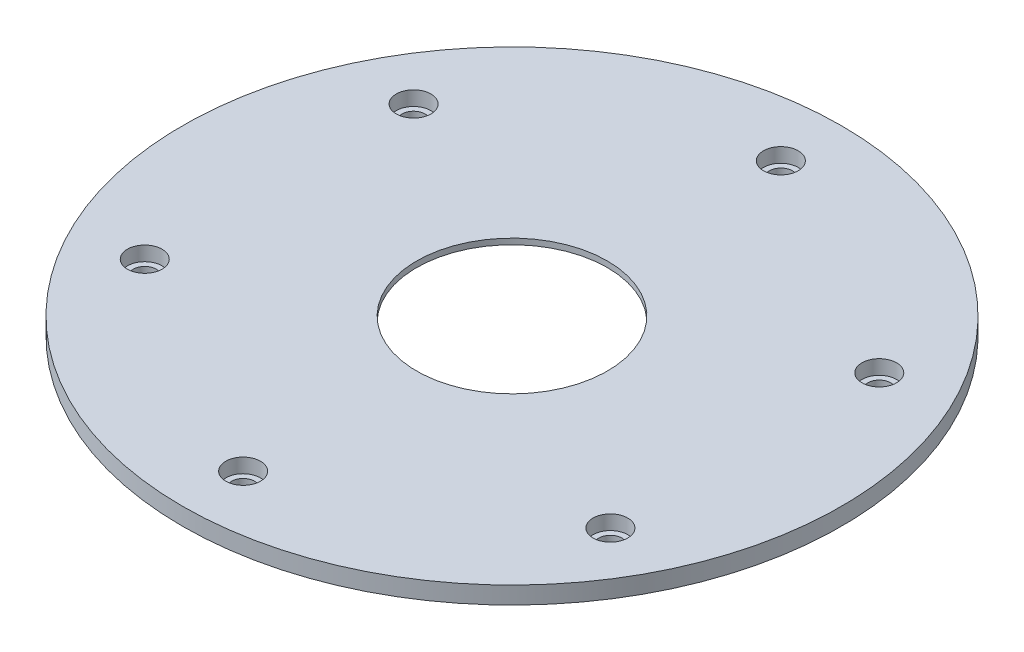
SolidWorks part; units mm, degrees
ref_plane "Front Plane" through (0, 0, 0) normal (0, 0, 1) x (1, 0, 0)
ref_plane "Top Plane" through (0, 0, 0) normal (0, 1, 0) x (1, 0, 0)
ref_plane "Right Plane" through (0, 0, 0) normal (1, 0, 0) x (0, 0, -1)
sketch "Sketch1" plane through (0, 0, 0) normal (0, 1, 0) x (1, 0, 0)
  circle A0 centre (0, 0) radius 57
  dimension "D1" = 114
extrude "Boss-Extrude1" add sketch "Sketch1" along normal blind 3
sketch "Sketch2" plane through (0, 3, 0) normal (0, 1, 0) x (1, 0, 0)
  line L0 (0, 62.5097) -> (0, -64.2706) construction
  circle A0 centre (0, 46.5) radius 2
  dimension "D1" = 4
  dimension "D2" = 46.5
extrude "Cut-Extrude1" cut sketch "Sketch2" against normal through all
pattern_circular "CirPattern1" count 6 over 360 about axis through (0, 0, 0) along (0, 1, 0) of "Cut-Extrude1"
sketch "Sketch5" plane through (0, 0, 0) normal (0, -1, 0) x (1, 0, 0)
  circle A0 centre (0, 46.5) radius 3.25
  circle A1 centre (40.2702, 23.25) radius 3.25
  circle A2 centre (40.2702, -23.25) radius 3.25
  circle A3 centre (0, -46.5) radius 3.25
  circle A4 centre (-40.2702, -23.25) radius 3.25
  circle A5 centre (-40.2702, 23.25) radius 3.25
  dimension "D1" = 6.5
  dimension "D2" = 6.5
extrude "Boss-Extrude2" add sketch "Sketch5" along normal blind 5
sketch "Sketch4" plane through (0, 0, 0) normal (0, -1, 0) x (1, 0, 0)
  circle A0 centre (0, 0) radius 16.5
  dimension "D1" = 33
extrude "Cut-Extrude3" cut sketch "Sketch4" against normal through all
sketch "Sketch8" plane through (0, 3, 0) normal (0, 1, 0) x (1, 0, 0)
  circle A0 centre (-40.2702, -23.25) radius 2 construction
  circle A1 centre (0, -46.5) radius 2 construction
  circle A2 centre (40.2702, -23.25) radius 2 construction
  circle A3 centre (40.2702, 23.25) radius 2 construction
  circle A4 centre (0, 46.5) radius 2 construction
  circle A5 centre (-40.2702, 23.25) radius 2 construction
  circle A6 centre (-40.2702, -23.25) radius 2
  circle A7 centre (0, -46.5) radius 2
  circle A8 centre (40.2702, -23.25) radius 2
  circle A9 centre (40.2702, 23.25) radius 2
  circle A10 centre (0, 46.5) radius 2
  circle A11 centre (-40.2702, 23.25) radius 2
extrude "Cut-Extrude4" cut sketch "Sketch8" against normal through all
sketch "Sketch9" plane through (0, 3, 0) normal (0, 1, 0) x (1, 0, 0)
  circle A0 centre (-40.2702, 23.25) radius 3
  circle A1 centre (0, 46.5) radius 3
  circle A2 centre (40.2702, 23.25) radius 3
  circle A3 centre (40.2702, -23.25) radius 3
  circle A4 centre (0, -46.5) radius 3
  circle A5 centre (-40.2702, -23.25) radius 3
  dimension "D1" = 6
extrude "Cut-Extrude5" cut sketch "Sketch9" against normal blind 2.5
sketch "Sketch11" plane through (0, 0, 0) normal (0, -1, 0) x (1, 0, 0)
  line L0 (0, 0) -> (0, 60.7001) construction
  line L1 (0, 0) -> (62.0393, 35.8184) construction
  arc A2 (-50.0231, 17.5126) -> (-50.0231, -17.5126) centre (0, 0) ccw
  circle A3 centre (0, 0) radius 57 construction
  arc A5 (5.1661, 47.4349) -> (9.8452, 52.0776) centre (9.1022, 48.1472) cw
  circle A6 centre (0, 46.5) radius 5.25
  arc A7 (-5.1661, 47.4349) -> (5.1661, 47.4349) centre (0, 46.5) ccw
  arc A8 (-5.1661, 47.4349) -> (-9.8452, 52.0776) centre (-9.1022, 48.1472) ccw
  arc A9 (38.4968, 28.1914) -> (40.1779, 34.565) centre (37.1456, 31.9563) ccw
  arc A10 (38.4968, 28.1914) -> (43.6629, 19.2435) centre (40.2702, 23.25) ccw
  arc A11 (43.6629, 19.2435) -> (50.0231, 17.5126) centre (46.2478, 16.1909) cw
  arc A12 (43.6629, -19.2435) -> (50.0231, -17.5126) centre (46.2478, -16.1909) ccw
  arc A13 (43.6629, -19.2435) -> (38.4968, -28.1914) centre (40.2702, -23.25) ccw
  arc A14 (38.4968, -28.1914) -> (40.1779, -34.565) centre (37.1456, -31.9563) cw
  arc A15 (5.1661, -47.4349) -> (9.8452, -52.0776) centre (9.1022, -48.1472) ccw
  arc A16 (5.1661, -47.4349) -> (-5.1661, -47.4349) centre (0, -46.5) ccw
  arc A17 (-5.1661, -47.4349) -> (-9.8452, -52.0776) centre (-9.1022, -48.1472) cw
  arc A18 (-38.4968, -28.1914) -> (-40.1779, -34.565) centre (-37.1456, -31.9563) ccw
  arc A19 (-38.4968, -28.1914) -> (-43.6629, -19.2435) centre (-40.2702, -23.25) ccw
  arc A20 (-43.6629, -19.2435) -> (-50.0231, -17.5126) centre (-46.2478, -16.1909) cw
  arc A21 (-43.6629, 19.2435) -> (-50.0231, 17.5126) centre (-46.2478, 16.1909) ccw
  arc A22 (-43.6629, 19.2435) -> (-38.4968, 28.1914) centre (-40.2702, 23.25) ccw
  arc A23 (-38.4968, 28.1914) -> (-40.1779, 34.565) centre (-37.1456, 31.9563) cw
  arc A24 (-9.8452, 52.0776) -> (-40.1779, 34.565) centre (0, 0) ccw
  arc A25 (40.1779, 34.565) -> (9.8452, 52.0776) centre (0, 0) ccw
  arc A26 (50.0231, -17.5126) -> (50.0231, 17.5126) centre (0, 0) ccw
  arc A27 (9.8452, -52.0776) -> (40.1779, -34.565) centre (0, 0) ccw
  arc A28 (-40.1779, -34.565) -> (-9.8452, -52.0776) centre (0, 0) ccw
  point P52 (0, 0)
  dimension "D2" = 4
  dimension "D3" = 2
  dimension "D4" = 4
  dimension "D5" = 4
  dimension "D1" = 60
  dimension "D6" = 6
extrude "Cut-Extrude7" cut sketch "Sketch11" against normal blind 2
pattern_circular "CirPattern3" count 6 over 360 of "Cut-Extrude7"
sketch "Sketch12" plane through (0, 2, 0) normal (0, -1, 0) x (1, 0, 0)
  circle A0 centre (0, 0) radius 25
  circle A1 centre (0, 0) radius 22.5
  dimension "D1" = 50
  dimension "D2" = 45
extrude "Boss-Extrude3" add sketch "Sketch12" along normal blind 2
